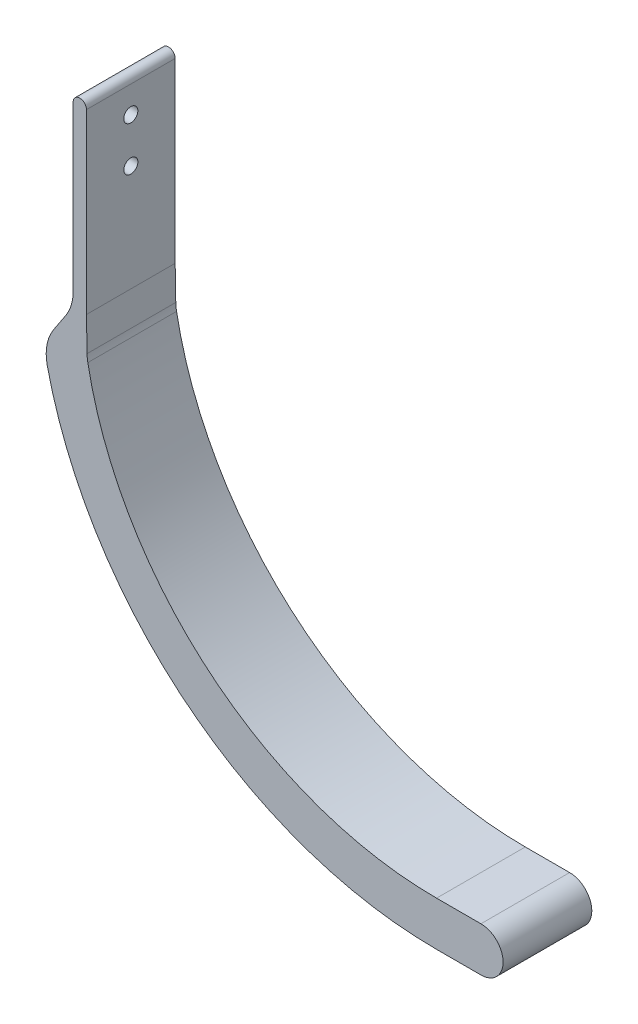
SolidWorks part; units mm, degrees
ref_plane "Front Plane" through (0, 0, 0) normal (0, 0, 1) x (1, 0, 0)
ref_plane "Top Plane" through (0, 0, 0) normal (0, 1, 0) x (1, 0, 0)
ref_plane "Right Plane" through (0, 0, 0) normal (1, 0, 0) x (0, 0, -1)
ref_plane "Plane1" through (0, 0, 20) normal (0, 0, 1) x (1, 0, 0)
sketch "Sketch1" plane through (0, 0, 20) normal (0, 0, 1) x (1, 0, 0)
  line L0 (-121.0343, -152.4616) -> (-121.1862, -144.0777)
  line L1 (-121.1862, -144.0777) -> (-121.1862, -104.0777)
  line L2 (-124.1862, -104.0777) -> (-124.1862, -144.0777)
  line L3 (-124.1862, -144.0777) -> (-130.8824, -154.1981)
  line L4 (-42.2497, -228.5698) -> (-32.2497, -228.5698)
  line L5 (-32.2497, -218.5698) -> (-42.2497, -218.5698)
  arc A0 (-121.1862, -104.0777) -> (-124.1862, -104.0777) centre (-122.6862, -104.0777) ccw
  arc A1 (-130.8824, -154.1981) -> (-42.2497, -228.5698) centre (-42.2497, -138.5698) ccw
  arc A2 (-32.2497, -228.5698) -> (-32.2497, -218.5698) centre (-32.2497, -223.5698) ccw
  arc A3 (-42.2497, -218.5698) -> (-121.0343, -152.4616) centre (-42.2497, -138.5698) cw
extrude "Boss-Extrude1" add sketch "Sketch1" against normal blind 20
hole_wizard "1/8 (0.125) Diameter Hole1" positions "Sketch3" profile "Sketch2" hole size "1/8" standard "ANSI Inch"
sketch "Sketch3" plane through (-121.1862, 0, 0) normal (1, 0, 0) x (0, 0, -1)
  point P0 (-10, -120.0777)
  point P1 (-10, -110.0777)
  dimension "D1" = 10
sketch "Sketch2" plane through (-121.1862, -120.0777, 10) normal (0, 1, 0) x (0, 0, -1)
  line L0 (0, 0) -> (0, 9.6962)
  line L1 (0, 9.6962) -> (1.5875, 9.6962)
  line L2 (1.5875, 9.6962) -> (1.5875, 0)
  line L5 (1.5875, 0) -> (0, 0)
  line L11 (0, -6.35) -> (0, 107.95) construction
  dimension "Thru Hole Dia." = 3.175
  dimension "Thru Hole Depth" = 9.6962
fillet "Fillet1" radius 10 3 edges at (-121.0343, -152.4616, 10) (-130.8824, -154.1981, 10) (-124.1862, -144.0777, 10)
